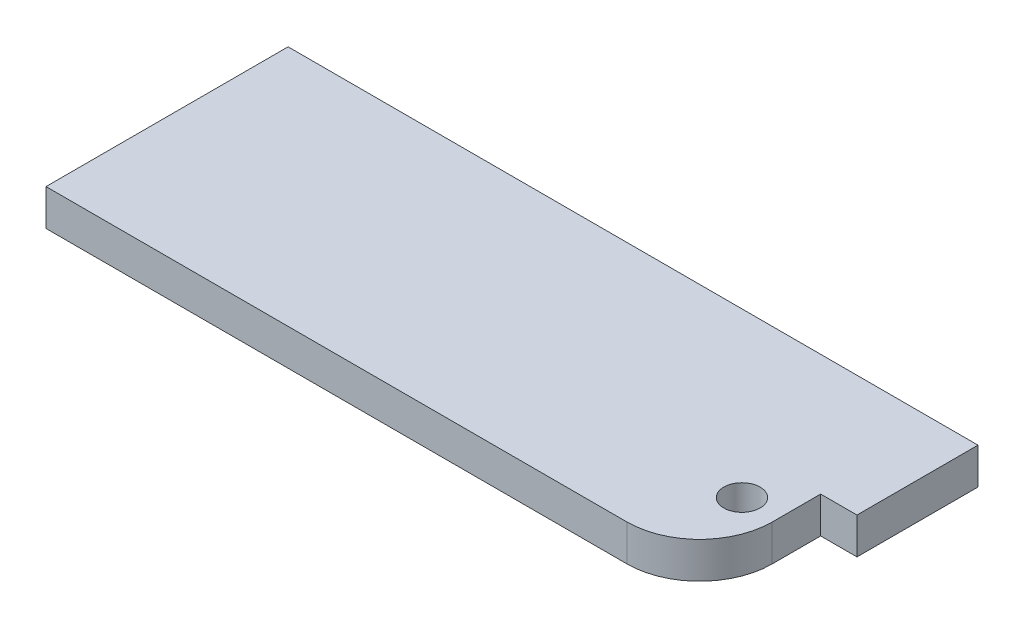
SolidWorks part; units mm, degrees
ref_plane "Front Plane" through (0, 0, 0) normal (0, 0, 1) x (1, 0, 0)
ref_plane "Top Plane" through (0, 0, 0) normal (0, 1, 0) x (1, 0, 0)
ref_plane "Right Plane" through (0, 0, 0) normal (1, 0, 0) x (0, 0, -1)
sketch "Sketch1" plane through (0, 0, 0) normal (0, 1, 0) x (1, 0, 0)
  line L1 (27, 10) -> (-27, 10)
  line L2 (27, 0) -> (27, -4)
  line L3 (21, -10) -> (-27, -10)
  line L4 (-27, 10) -> (-27, -10)
  line L5 (27, 10) -> (-27, -10) construction
  line L6 (27, -10) -> (-27, 10) construction
  line L7 (27, 10) -> (30, 10)
  line L9 (27, 0) -> (30, 0)
  line L10 (30, 10) -> (30, 0)
  arc A0 (21, -10) -> (27, -4) centre (21, -4) ccw
  circle A1 centre (24, -3.5) radius 1.5
  point P0 (0, 0)
  dimension "D3" = 12
  dimension "D6" = 3
  dimension "D1" = 20
  dimension "D2" = 54
  dimension "D4" = 10
  dimension "D5" = 3
  dimension "D7" = 13.5
  dimension "D8" = 3
extrude "Boss-Extrude1" add sketch "Sketch1" along normal blind 3
